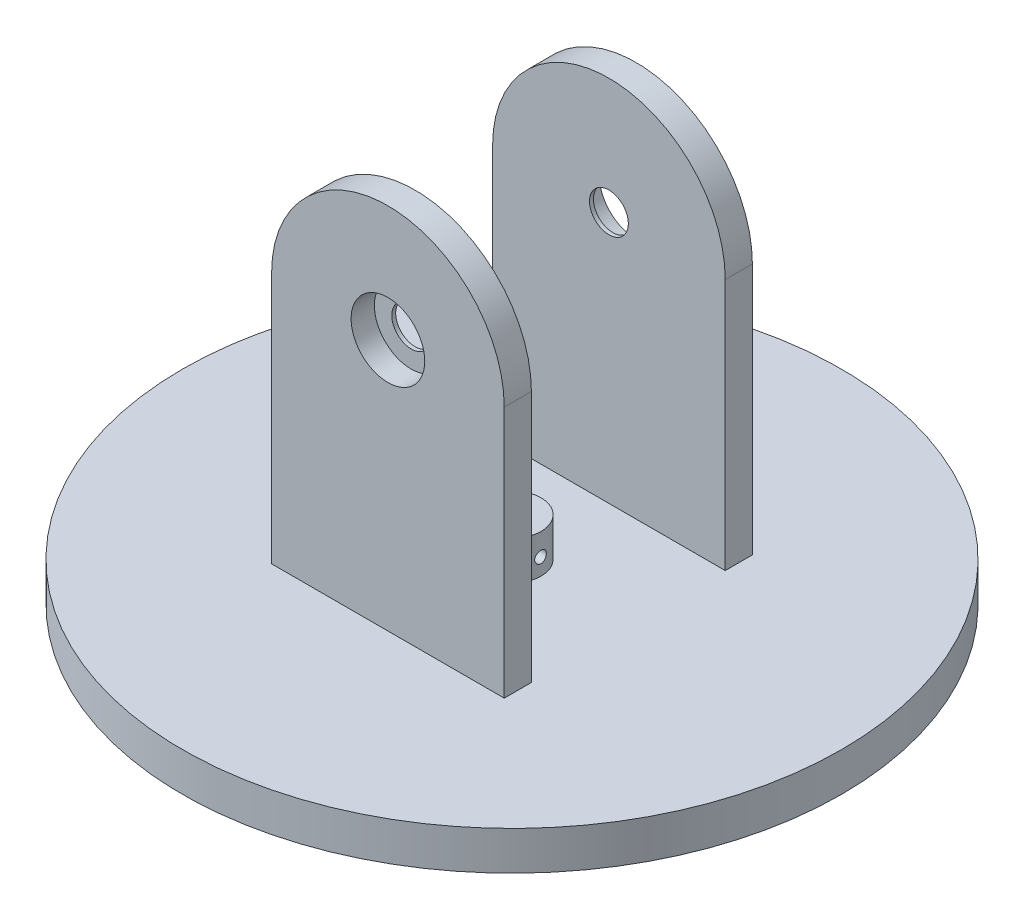
SolidWorks part; units mm, degrees
material "6061 Alloy"
ref_plane "Front Plane" through (0, 0, 0) normal (0, 0, 1) x (1, 0, 0)
ref_plane "Top Plane" through (0, 0, 0) normal (0, 1, 0) x (1, 0, 0)
ref_plane "Right Plane" through (0, 0, 0) normal (1, 0, 0) x (0, 0, -1)
sketch "Sketch1" plane through (0, 0, 0) normal (0, 0, 1) x (1, 0, 0)
  line L0 (-30, 0) -> (30, 0)
  line L1 (-30, 65) -> (-30, 0)
  line L2 (30, 65) -> (30, 0)
  arc A0 (30, 65) -> (-30, 65) centre (0, 65) ccw
  dimension "D2" = 30
  dimension "D1" = 65
extrude "Boss-Extrude1" add sketch "Sketch1" along normal mid plane 64
sketch "Sketch5" plane through (0, 0, 32) normal (0, 0, 1) x (1, 0, 0)
  circle A0 centre (0, 65) radius 9.5
  dimension "D1" = 19
extrude "Cut-Extrude2" cut sketch "Sketch5" against normal blind 6
sketch "Sketch12" plane through (0, 0, -32) normal (0, 0, -1) x (-1, 0, 0)
  circle A0 centre (0, 65) radius 9.5
  dimension "D1" = 19
extrude "Cut-Extrude5" cut sketch "Sketch12" against normal blind 6
sketch "Sketch8" plane through (-30, 0, 0) normal (-1, 0, 0) x (0, 0, 1)
  line L0 (32, 95) -> (-32, 95) construction
  line L1 (25, 0) -> (-25, 0)
  line L2 (25, 0) -> (25, 95)
  line L3 (25, 95) -> (-25, 95)
  line L4 (-25, 0) -> (-25, 95)
  line L5 (25, 0) -> (-25, 95) construction
  line L6 (25, 95) -> (-25, 0) construction
  line L8 (0, 0) -> (0, 49.7124) construction
  point P0 (0, 47.5)
  dimension "D1" = 50
extrude "Cut-Extrude3" cut sketch "Sketch8" against normal through all
sketch "Sketch6" plane through (0, 0, 0) normal (0, 0, 1) x (1, 0, 0)
  line L0 (7.5, 0) -> (85, 0)
  line L1 (85, 0) -> (85, -10)
  line L6 (85, -10) -> (35, -10)
  line L8 (25, -5) -> (35, -5)
  line L9 (0, -9.4449) -> (0, 25.8349) construction
  line L10 (35, -5) -> (35, -10)
  line L13 (3, -15) -> (25, -15)
  line L14 (25, -15) -> (25, -5)
  line L15 (7.5, 0) -> (7.5, 10)
  line L16 (7.5, 10) -> (3, 10)
  line L17 (3, 10) -> (3, -15)
  dimension "D1" = 170
  dimension "D2" = 70
  dimension "D3" = 6
  dimension "D4" = 5
  dimension "D5" = 5
  dimension "D6" = 50
  dimension "D7" = 10
  dimension "D8" = 10
  dimension "D9" = 15
revolve "Revolve1" add sketch "Sketch6" angle 360 about L9
ref_plane "Plane1" through (7.5, 0, 0) normal (1, 0, 0) x (0, 0, -1)
sketch "Sketch10" plane through (7.5, 0, 0) normal (1, 0, 0) x (0, 0, -1)
  line L0 (7.5, 10) -> (-7.5, 10) construction
  circle A0 centre (0, 4.3) radius 1.5
  dimension "D1" = 3
  dimension "D2" = 5.7
extrude "Cut-Extrude4" cut sketch "Sketch10" against normal through all
fillet "Fillet1" radius 1 1 edges at (25, -15, 0)
sketch "Sketch13" plane through (0, 0, 26) normal (0, 0, 1) x (1, 0, 0)
  circle A0 centre (0, 65) radius 5
  dimension "D1" = 10
extrude "Cut-Extrude6" cut sketch "Sketch13" against normal through all
